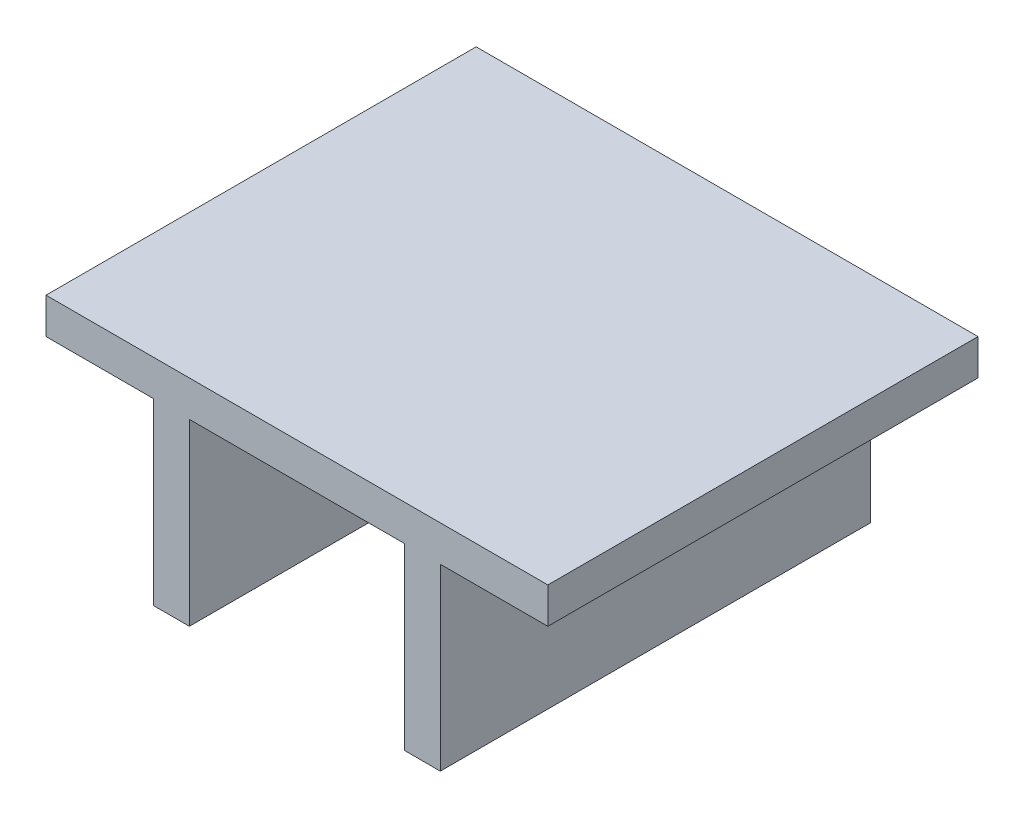
SolidWorks part; units mm, degrees
ref_plane "Front Plane" through (0, 0, 0) normal (0, 0, 1) x (1, 0, 0)
ref_plane "Top Plane" through (0, 0, 0) normal (0, 1, 0) x (1, 0, 0)
ref_plane "Right Plane" through (0, 0, 0) normal (1, 0, 0) x (0, 0, -1)
sketch "Sketch1" plane through (0, 0, 0) normal (0, 0, 1) x (1, 0, 0)
  line L0 (0, 0) -> (0, -6.35)
  line L1 (0, 0) -> (88.9, 0)
  line L2 (0, 0) -> (0, -38.1)
  line L3 (0, -38.1) -> (88.9, -38.1)
  line L4 (88.9, 0) -> (88.9, -38.1)
  line L5 (0, -6.35) -> (88.9, -6.35)
  line L6 (0, -38.1) -> (25.4, -38.1)
  line L7 (25.4, -38.1) -> (63.5, -38.1)
  line L8 (25.4, -38.1) -> (25.4, -6.35)
  line L9 (63.5, -38.1) -> (63.5, -6.35)
  line L10 (25.4, -38.1) -> (19.05, -38.1)
  line L11 (19.05, -38.1) -> (19.05, -6.35)
  line L12 (63.5, -38.1) -> (69.85, -38.1)
  line L13 (69.85, -38.1) -> (69.85, -6.35)
  dimension "D1" = 88.9
  dimension "D2" = 38.1
  dimension "D3" = 6.35
  dimension "D4" = 25.4
  dimension "D5" = 38.1
  dimension "D6" = 6.35
  dimension "D7" = 6.35
extrude "Boss-Extrude1" add sketch "Sketch1" along normal blind 76.2 contours L0 L5 L4 L1 | L11 L6 L8 L5 | L3 L13 L5 L9
